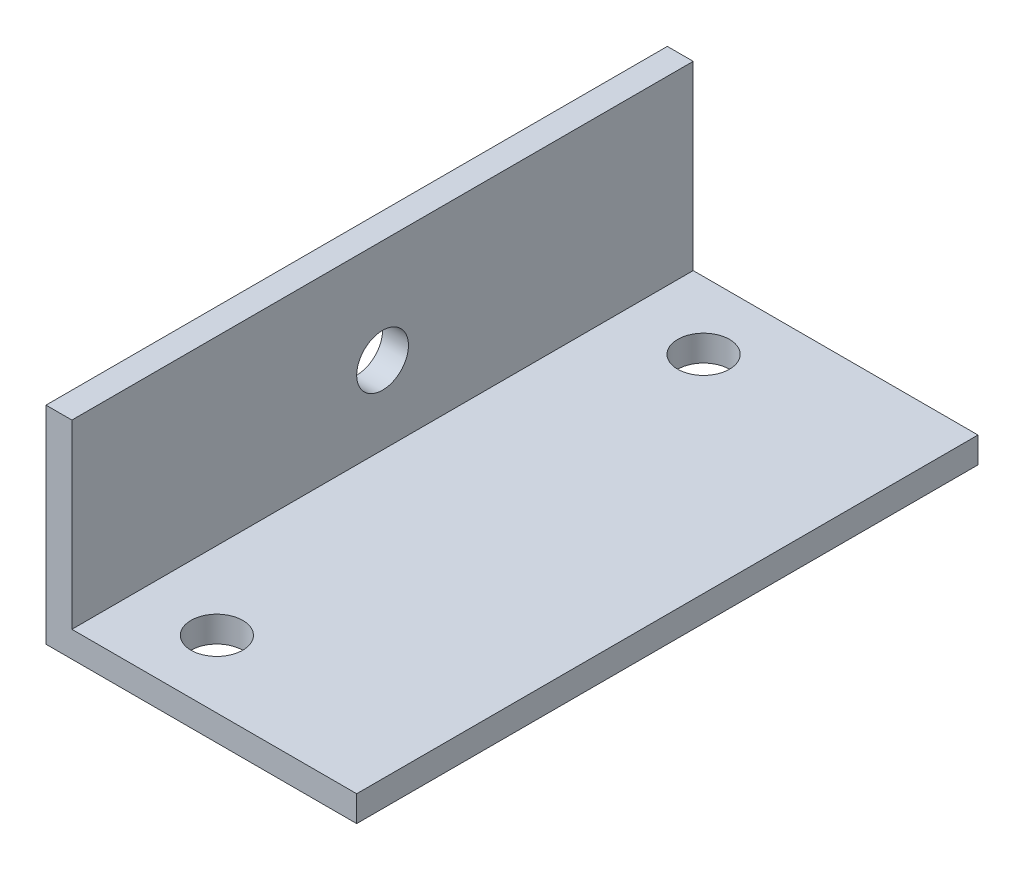
SolidWorks part; units mm, degrees
material "6063-T5"
ref_plane "Front Plane" through (0, 0, 0) normal (0, 0, 1) x (1, 0, 0)
ref_plane "Top Plane" through (0, 0, 0) normal (0, 1, 0) x (1, 0, 0)
ref_plane "Right Plane" through (0, 0, 0) normal (1, 0, 0) x (0, 0, -1)
sketch "Sketch1" plane through (0, 0, 0) normal (0, 0, 1) x (1, 0, 0)
  line L0 (0, 12.7) -> (0, 0)
  line L1 (0, 0) -> (19.05, 0)
  line L2 (0, 12.7) -> (1.5875, 12.7)
  line L3 (1.5875, 12.7) -> (1.5875, 1.5875)
  line L4 (1.5875, 1.5875) -> (19.05, 1.5875)
  line L5 (19.05, 1.5875) -> (19.05, 0)
  dimension "D1" = 12.7
  dimension "D2" = 19.05
  dimension "D3" = 1.5875
  dimension "D4" = 1.5875
extrude "Boss-Extrude1" add sketch "Sketch1" along normal blind 38.1
sketch "Sketch2" plane through (0, 0, 0) normal (-1, 0, 0) x (0, 0, 1)
  line L0 (19.05, 12.7) -> (19.05, 0) construction
  line L1 (38.1, 12.7) -> (0, 12.7) construction
  line L2 (38.1, 0) -> (0, 0) construction
  circle A0 centre (19.05, 6.35) radius 1.5875
  dimension "D1" = 3.175
  dimension "D3" = 6.35
extrude "Cut-Extrude1" cut sketch "Sketch2" against normal through all
sketch "Sketch3" plane through (0, 0, 0) normal (0, -1, 0) x (1, 0, 0)
  line L0 (0, 19.05) -> (19.05, 19.05) construction
  line L1 (0, 38.1) -> (0, 0) construction
  line L2 (19.05, 38.1) -> (19.05, 0) construction
  circle A0 centre (6.35, 4.1275) radius 1.5875
  circle A1 centre (6.35, 33.9725) radius 1.5875
  dimension "D1" = 3.175
  dimension "D2" = 6.35
  dimension "D3" = 14.9225
extrude "Cut-Extrude2" cut sketch "Sketch3" against normal through all
